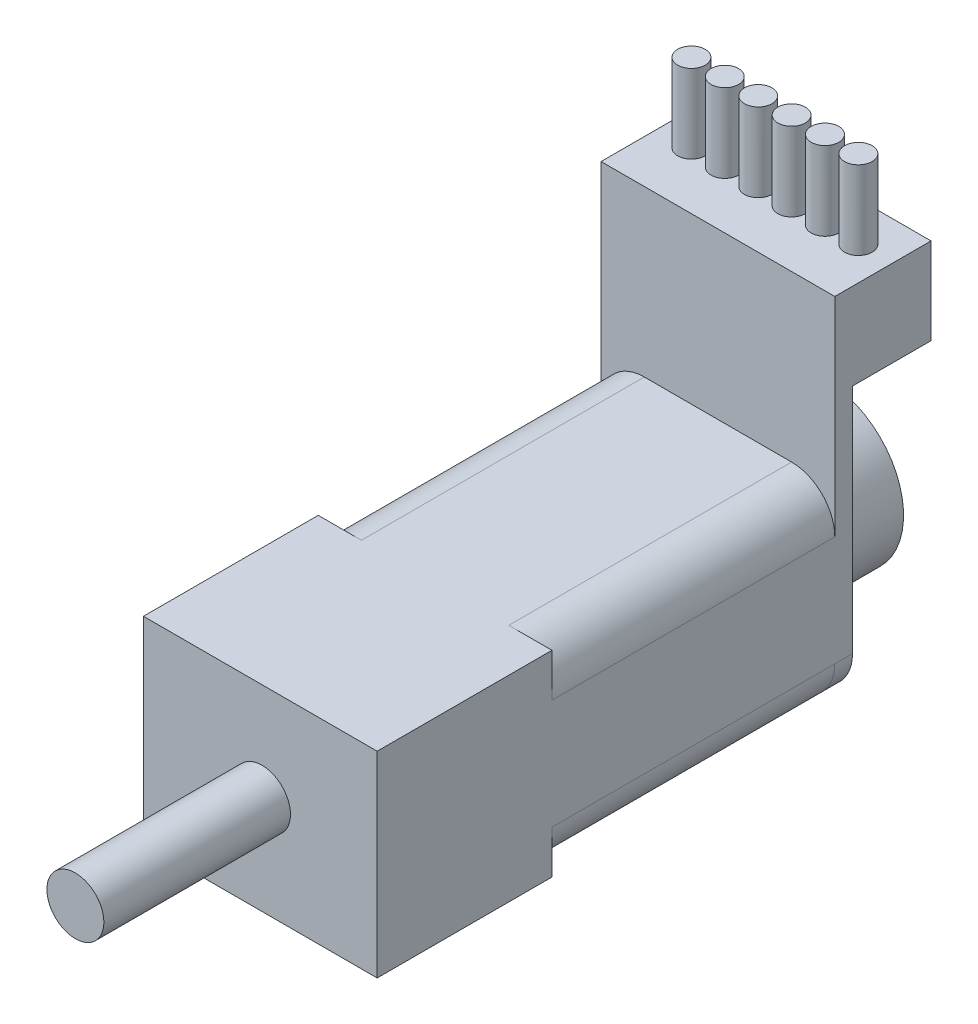
SolidWorks part; units mm, degrees
ref_plane "Front Plane" through (0, 0, 0) normal (0, 0, 1) x (1, 0, 0)
ref_plane "Top Plane" through (0, 0, 0) normal (0, 1, 0) x (1, 0, 0)
ref_plane "Right Plane" through (0, 0, 0) normal (1, 0, 0) x (0, 0, -1)
sketch "Sketch3" plane through (0, 0, 0) normal (0, 0, 1) x (1, 0, 0)
  line L1 (0, 0) -> (11.9, 0)
  line L2 (0, 0) -> (0, 10)
  line L3 (0, 10) -> (11.9, 10)
  line L4 (11.9, 0) -> (11.9, 10)
  dimension "D1" = 11.9
  dimension "D2" = 10
extrude "Boss-Extrude1" add sketch "Sketch3" along normal blind 14.4
fillet "Fillet6" radius 2.2 4 edges at (0, 0, 7.2) (0, 10, 7.2) (11.9, 0, 7.2) (11.9, 10, 7.2)
sketch "Sketch6" plane through (0, 0, 14.4) normal (0, 0, 1) x (1, 0, 0)
  line L1 (0, 0) -> (11.9, 0)
  line L2 (0, 0) -> (0, 10)
  line L3 (0, 10) -> (11.9, 10)
  line L4 (11.9, 0) -> (11.9, 10)
  dimension "D1" = 10
  dimension "D2" = 11.9
extrude "Boss-Extrude2" add sketch "Sketch6" along normal blind 8.9
sketch "Sketch7" plane through (0, 0, 23.3) normal (0, 0, 1) x (1, 0, 0)
  line L0 (6.0352, 5) -> (6.0352, 0) construction
  line L1 (0, 0) -> (11.9, 0) construction
  line L2 (6.0352, 5) -> (0.0352, 5) construction
  circle A0 centre (6.0352, 5) radius 1.45
  dimension "D1" = 2.9
  dimension "D2" = 5
  dimension "D3" = 6
extrude "Boss-Extrude3" add sketch "Sketch7" along normal blind 9.5 contours A0
sketch "Sketch8" plane through (0, 0, 0) normal (0, 0, -1) x (-1, 0, 0)
  line L0 (-11.9, 0) -> (-11.9, 18.4)
  line L1 (-11.9, 0) -> (0, 0)
  line L2 (0, 0) -> (0, 18.4)
  line L3 (0, 18.4) -> (-11.9, 18.4)
  dimension "D1" = 18.4
extrude "Boss-Extrude4" add sketch "Sketch8" along normal blind 0.9
fillet "Fillet7" radius 2.2 2 edges at (0, 0, -0.45) (11.9, 0, -0.45)
sketch "Sketch9" plane through (0, 0, -0.9) normal (0, 0, -1) x (-1, 0, 0)
  line L0 (-5.9, 5) -> (-5.9, 0) construction
  line L1 (-9.7, 0) -> (-2.2, 0) construction
  line L2 (-5.9, 5) -> (-11.9, 5) construction
  line L3 (-11.9, 18.4) -> (-11.9, 2.2) construction
  circle A0 centre (-5.9, 5) radius 4
  dimension "D1" = 5
  dimension "D3" = 8
  dimension "D2" = 6
extrude "Boss-Extrude6" add sketch "Sketch9" along normal blind 4.6
sketch "Sketch10" plane through (0, 0, -0.9) normal (0, 0, -1) x (-1, 0, 0)
  line L0 (0, 2.2) -> (0, 18.4) construction
  line L1 (-11.9, 18.4) -> (0, 18.4)
  line L2 (-11.9, 18.4) -> (-11.9, 14)
  line L3 (-11.9, 14) -> (0, 14)
  line L4 (0, 18.4) -> (0, 14)
  dimension "D1" = 4.4
extrude "Boss-Extrude7" add sketch "Sketch10" along normal blind 4
sketch "Sketch11" plane through (0, 18.4, 0) normal (0, 1, 0) x (1, 0, 0)
  line L0 (6.8, 2.9) -> (6.8, 4.9) construction
  line L1 (0, 4.9) -> (11.9, 4.9) construction
  line L2 (6.8, 2.9) -> (11.9, 2.9) construction
  line L4 (11.9, 4.9) -> (11.9, 0) construction
  line L5 (0, 4.9) -> (0, 0) construction
  circle A0 centre (6.8, 2.9) radius 0.7
  circle A1 centre (8.5, 2.9) radius 0.7025
  circle A2 centre (10.2, 2.9) radius 0.701
  circle A3 centre (1.7, 2.9) radius 0.7
  circle A5 centre (5.1, 2.9) radius 0.7
  circle A6 centre (3.4, 2.9) radius 0.7
  dimension "D1" = 2
  dimension "D3" = 1.4
  dimension "D5" = 1.4049
  dimension "D6" = 1.4019
  dimension "D8" = 1.4
  dimension "D11" = 1.4
  dimension "D13" = 1.4
  dimension "D2" = 5.1
  dimension "D4" = 3.4
  dimension "D7" = 1.7
  dimension "D9" = 1.7
  dimension "D10" = 2
  dimension "D12" = 3.4
  dimension "D14" = 2
  dimension "D15" = 5.1
  dimension "D16" = 2
extrude "Boss-Extrude8" add sketch "Sketch11" along normal blind 4 contours A6 | A5 | A0 | A1 | A2 | A3
